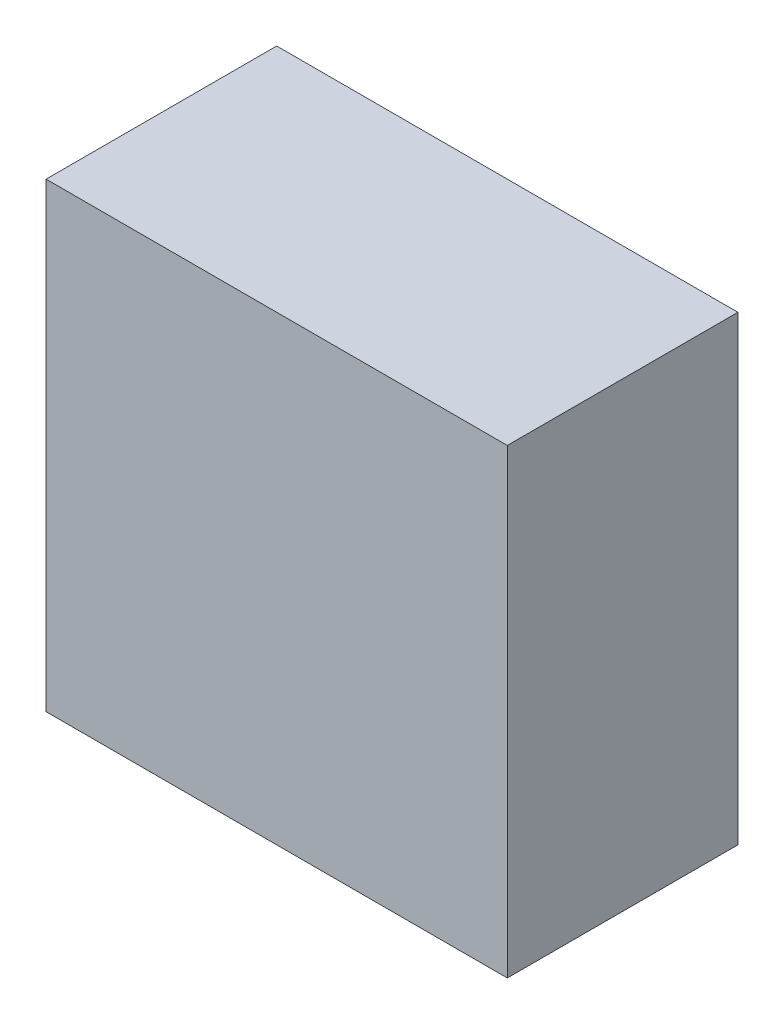
SolidWorks part; units mm, degrees
ref_plane "Přední rovina" through (0, 0, 0) normal (0, 0, 1) x (1, 0, 0)
ref_plane "Horní rovina" through (0, 0, 0) normal (0, 1, 0) x (1, 0, 0)
ref_plane "Pravá rovina" through (0, 0, 0) normal (1, 0, 0) x (0, 0, -1)
sketch "Skica1" plane through (0, 0, 0) normal (0, 0, 1) x (1, 0, 0)
  line L1 (-10, -10) -> (10, -10)
  line L2 (-10, -10) -> (-10, 10)
  line L3 (-10, 10) -> (10, 10)
  line L4 (10, -10) -> (10, 10)
  line L5 (-10, -10) -> (10, 10) construction
  line L6 (-10, 10) -> (10, -10) construction
  point P0 (0, 0)
  dimension "D1" = 20
  dimension "D2" = 20
extrude "Přidat vysunutím1" add sketch "Skica1" along normal blind 10
sketch "Skica2" plane through (0, 0, 0) normal (0, 0, -1) x (-1, 0, 0)
  line L1 (-8.5, -8.5) -> (8.5, -8.5)
  line L2 (-8.5, -8.5) -> (-8.5, 8.5)
  line L3 (-8.5, 8.5) -> (8.5, 8.5)
  line L4 (8.5, -8.5) -> (8.5, 8.5)
  line L5 (-8.5, -8.5) -> (8.5, 8.5) construction
  line L6 (-8.5, 8.5) -> (8.5, -8.5) construction
  point P0 (0, 0)
  dimension "D1" = 17
  dimension "D2" = 17
extrude "Odebrat vysunutím1" cut sketch "Skica2" against normal blind 7.5
sketch "Skica3" plane through (0, 0, 7.5) normal (0, 0, -1) x (-1, 0, 0)
  circle A0 centre (0, 0) radius 2.65
  dimension "D1" = 5.3
extrude "Přidat vysunutím2" add sketch "Skica3" along normal blind 7.5
sketch "Skica4" plane through (0, 0, 0) normal (0, 0, -1) x (-1, 0, 0)
  line L0 (-0.65, 2.15) -> (0.65, 2.15)
  line L1 (0.65, 2.15) -> (0.65, 0.65)
  line L2 (0.65, 0.65) -> (2.15, 0.65)
  line L3 (2.15, 0.65) -> (2.15, -0.65)
  line L4 (0, 0) -> (0, 2.65) construction
  line L5 (-2.15, 0.65) -> (-2.15, -0.65)
  line L6 (-0.65, 0.65) -> (-2.15, 0.65)
  line L7 (-0.65, 2.15) -> (-0.65, 0.65)
  line L8 (0, 0) -> (2.65, 0) construction
  line L9 (0.65, -0.65) -> (2.15, -0.65)
  line L10 (0.65, -2.15) -> (0.65, -0.65)
  line L11 (-0.65, -2.15) -> (0.65, -2.15)
  line L12 (-0.65, -2.15) -> (-0.65, -0.65)
  line L13 (-0.65, -0.65) -> (-2.15, -0.65)
  circle A0 centre (0, 0) radius 2.65 construction
  circle A1 centre (0, 0) radius 2.65 construction
  point P15 (0, 2.15)
  point P19 (2.15, 0)
  point P24 (-2.15, 0)
  dimension "D1" = 0.65
  dimension "D2" = 0.65
  dimension "D3" = 2.15
  dimension "D4" = 2.15
extrude "Odebrat vysunutím2" cut sketch "Skica4" against normal blind 7.5
